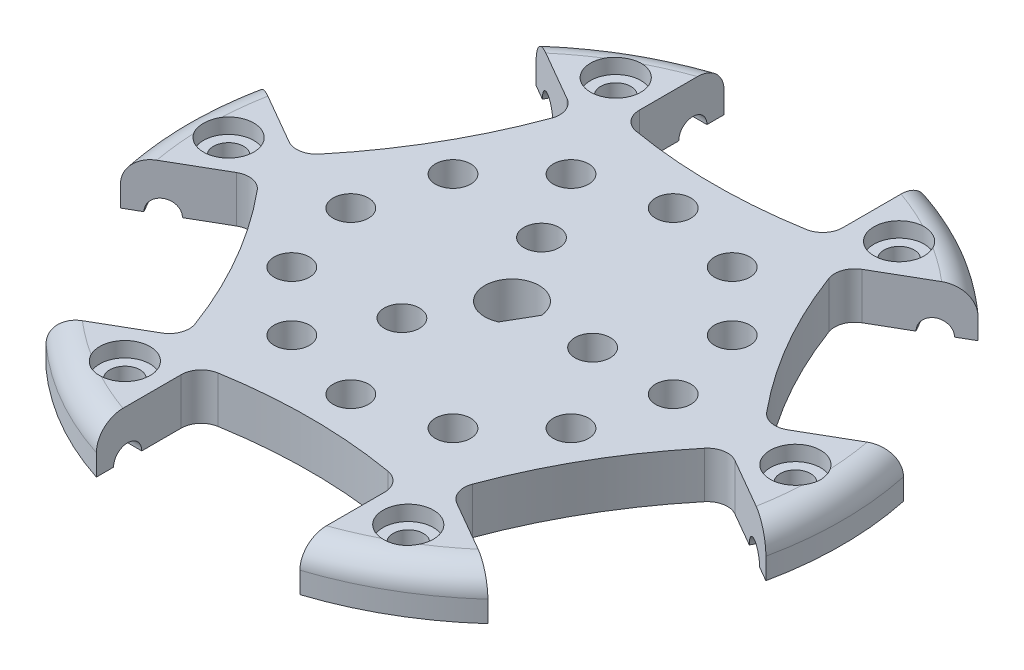
SolidWorks part; units mm, degrees
ref_plane "Plano frontal" through (0, 0, 0) normal (0, 0, 1) x (1, 0, 0)
ref_plane "Plano superior" through (0, 0, 0) normal (0, 1, 0) x (1, 0, 0)
ref_plane "Plano direito" through (0, 0, 0) normal (1, 0, 0) x (0, 0, -1)
sketch "Esboço1" plane through (0, 0, 0) normal (0, 0, 1) x (1, 0, 0)
  line L1 (-32.75, 2.1) -> (-32.75, 0)
  line L2 (-30.25, 4.6) -> (-6.07, 4.6)
  line L15 (-6.07, 4.6) -> (0, 4.6)
  line L17 (0, 0) -> (0, 4.6)
  line L18 (-32.75, 0) -> (0, 0)
  arc A3 (-30.25, 4.6) -> (-32.75, 2.1) centre (-30.25, 2.1) ccw
revolve "Revolução3" add sketch "Esboço1" angle 360 about L17
sketch "Esboço3" plane through (0, 0, 0) normal (0, -1, 0) x (1, 0, 0)
  line L2 (-10.1, 71.55) -> (10.1, 71.55)
  line L3 (-10.1, 71.55) -> (-10.1, 22.7384)
  line L4 (10.1, 71.55) -> (10.1, 22.7384)
  line L5 (10.1, -71.55) -> (-10.1, -71.55)
  line L6 (10.1, -71.55) -> (10.1, -22.7384)
  line L7 (-10.1, -71.55) -> (-10.1, -22.7384)
  line L10 (56.9141, 44.5219) -> (67.0141, 27.0281)
  line L11 (56.9141, 44.5219) -> (14.642, 20.116)
  line L12 (67.0141, 27.0281) -> (24.742, 2.6223)
  line L13 (-56.9141, -44.5219) -> (-67.0141, -27.0281)
  line L14 (-56.9141, -44.5219) -> (-14.642, -20.116)
  line L15 (-67.0141, -27.0281) -> (-24.742, -2.6223)
  line L18 (-67.0141, 27.0281) -> (-56.9141, 44.5219)
  line L19 (-67.0141, 27.0281) -> (-24.742, 2.6223)
  line L20 (-56.9141, 44.5219) -> (-14.642, 20.116)
  line L21 (67.0141, -27.0281) -> (56.9141, -44.5219)
  line L22 (67.0141, -27.0281) -> (24.742, -2.6223)
  line L23 (56.9141, -44.5219) -> (14.642, -20.116)
  arc A1 (-8.4375, 20.7671) -> (8.4375, 20.7671) centre (0, 70.05) ccw
  arc A2 (8.4375, 20.7671) -> (10.1, 22.7384) centre (8.1, 22.7384) ccw
  arc A3 (-8.4375, 20.7671) -> (-10.1, 22.7384) centre (-8.1, 22.7384) cw
  arc A4 (8.4375, -20.7671) -> (-8.4375, -20.7671) centre (0, -70.05) ccw
  arc A5 (-8.4375, -20.7671) -> (-10.1, -22.7384) centre (-8.1, -22.7384) ccw
  arc A6 (8.4375, -20.7671) -> (10.1, -22.7384) centre (8.1, -22.7384) cw
  arc A7 (13.766, 17.6906) -> (22.2035, 3.0764) centre (60.6651, 35.025) ccw
  arc A8 (22.2035, 3.0764) -> (24.742, 2.6223) centre (23.742, 4.3544) ccw
  arc A9 (13.766, 17.6906) -> (14.642, 20.116) centre (15.642, 18.384) cw
  arc A10 (-13.766, -17.6906) -> (-22.2035, -3.0764) centre (-60.6651, -35.025) ccw
  arc A11 (-22.2035, -3.0764) -> (-24.742, -2.6223) centre (-23.742, -4.3544) ccw
  arc A12 (-13.766, -17.6906) -> (-14.642, -20.116) centre (-15.642, -18.384) cw
  arc A13 (-22.2035, 3.0764) -> (-13.766, 17.6906) centre (-60.6651, 35.025) ccw
  arc A14 (-13.766, 17.6906) -> (-14.642, 20.116) centre (-15.642, 18.384) ccw
  arc A15 (-22.2035, 3.0764) -> (-24.742, 2.6223) centre (-23.742, 4.3544) cw
  arc A16 (22.2035, -3.0764) -> (13.766, -17.6906) centre (60.6651, -35.025) ccw
  arc A17 (13.766, -17.6906) -> (14.642, -20.116) centre (15.642, -18.384) ccw
  arc A18 (22.2035, -3.0764) -> (24.742, -2.6223) centre (23.742, -4.3544) cw
extrude "Corte-extrusão2" cut sketch "Esboço3" against normal blind 10
sketch "Esboço5" plane through (0, 0, 0) normal (0, -1, 0) x (1, 0, 0)
  line L0 (-12.6, 26.65) -> (12.6, 26.65)
  line L1 (-12.6, 28.05) -> (12.6, 28.05)
  line L10 (-12.6, 28.05) -> (-12.6, 26.65)
  line L13 (12.6, 28.05) -> (12.6, 26.65)
revolve "Corte-Revolução3" cut sketch "Esboço5" angle 360 about L1
sketch "Esboço6" plane through (0, 0, 0) normal (0, -1, 0) x (1, 0, 0)
  line L21 (-29.3796, 2.4131) -> (-16.7796, 24.2369)
  line L22 (-30.592, 3.1131) -> (-17.992, 24.9369)
  line L23 (-30.592, 3.1131) -> (-29.3796, 2.4131)
  line L24 (-17.992, 24.9369) -> (-16.7796, 24.2369)
revolve "Corte-Revolução4" cut sketch "Esboço6" angle 360 about L22
sketch "Esboço7" plane through (0, 0, 0) normal (0, -1, 0) x (1, 0, 0)
  line L9 (-16.7796, -24.2369) -> (-29.3796, -2.4131)
  line L10 (-17.992, -24.9369) -> (-30.592, -3.1131)
  line L11 (-17.992, -24.9369) -> (-16.7796, -24.2369)
  line L12 (-30.592, -3.1131) -> (-29.3796, -2.4131)
revolve "Corte-Revolução5" cut sketch "Esboço7" angle 360 about L10
sketch "Esboço8" plane through (0, 0, 0) normal (0, -1, 0) x (1, 0, 0)
  line L13 (16.7796, 24.2369) -> (29.3796, 2.4131)
  line L14 (17.992, 24.9369) -> (30.592, 3.1131)
  line L15 (17.992, 24.9369) -> (16.7796, 24.2369)
  line L16 (30.592, 3.1131) -> (29.3796, 2.4131)
revolve "Corte-Revolução6" cut sketch "Esboço8" angle 360 about L14
sketch "Esboço10" plane through (0, 0, 0) normal (0, -1, 0) x (1, 0, 0)
  line L1 (12.6, -26.65) -> (-12.6, -26.65)
  line L2 (12.6, -28.05) -> (-12.6, -28.05)
  line L3 (12.6, -28.05) -> (12.6, -26.65)
  line L4 (-12.6, -28.05) -> (-12.6, -26.65)
revolve "Corte-Revolução7" cut sketch "Esboço10" angle 360 about L2
sketch "Esboço11" plane through (0, 0, 0) normal (0, -1, 0) x (1, 0, 0)
  line L5 (29.3796, -2.4131) -> (16.7796, -24.2369)
  line L6 (30.592, -3.1131) -> (17.992, -24.9369)
  line L7 (30.592, -3.1131) -> (29.3796, -2.4131)
  line L8 (17.992, -24.9369) -> (16.7796, -24.2369)
revolve "Corte-Revolução8" cut sketch "Esboço11" angle 360 about L6
sketch "Esboço12" plane through (0, 0, 0) normal (0, -1, 0) x (1, 0, 0)
  circle A1 centre (0, 16) radius 1.75
  circle A2 centre (-8, 13.8564) radius 1.75
  circle A3 centre (-13.8564, 8) radius 1.75
  circle A4 centre (-16, 0) radius 1.75
  circle A5 centre (-13.8564, -8) radius 1.75
  circle A6 centre (-8, -13.8564) radius 1.75
  circle A7 centre (0, -16) radius 1.75
  circle A8 centre (8, -13.8564) radius 1.75
  circle A9 centre (13.8564, -8) radius 1.75
  circle A10 centre (16, 0) radius 1.75
  circle A11 centre (13.8564, 8) radius 1.75
  circle A12 centre (8, 13.8564) radius 1.75
  circle A13 centre (28.1296, 0) radius 1.3
  circle A14 centre (14.0648, 24.3609) radius 1.3
  circle A15 centre (-14.0648, 24.3609) radius 1.3
  circle A16 centre (-28.1296, 0) radius 1.3
  circle A18 centre (14.0648, -24.3609) radius 1.3
  circle A19 centre (-14.0648, -24.3609) radius 1.3
sketch "Esboço14" plane through (0, 0, 0) normal (0, -1, 0) x (1, 0, 0)
  line L2 (1.0522, 2.3776) -> (2.5851, -0.2776)
  arc A0 (1.0522, 2.3776) -> (2.5851, -0.2776) centre (0, 0) ccw
extrude "Corte-extrusão7" cut sketch "Esboço12" against normal through all
sketch "Esboço15" plane through (0, 4.6, 0) normal (0, 1, 0) x (1, 0, 0)
  line L0 (0, 0) -> (-1.5171, -0.4065)
  circle A0 centre (-4, -6.9282) radius 1.75
  circle A1 centre (8, 0) radius 1.75
  circle A2 centre (-4, 6.9282) radius 1.75
extrude "Corte-extrusão8" cut sketch "Esboço15" against normal through all contours A0 | A1 | A2
extrude "Corte-extrusão9" cut sketch "Esboço14" against normal through all
sketch "Esboço16" plane through (0, 4.6, 0) normal (0, 1, 0) x (1, 0, 0)
  circle A0 centre (-14.0648, 24.3609) radius 2.05
  circle A1 centre (-28.1296, 0) radius 2.05
  circle A2 centre (-14.0648, -24.3609) radius 2.05
  circle A3 centre (14.0648, -24.3609) radius 2.05
  circle A4 centre (28.1296, 0) radius 2.05
  circle A5 centre (14.0648, 24.3609) radius 2.05
extrude "Corte-extrusão10" cut sketch "Esboço16" against normal blind 1.5
sketch "Esboço17" plane through (0, 4.6, 0) normal (0, 1, 0) x (1, 0, 0)
  circle A0 centre (-14.0648, 24.3609) radius 1.5
  circle A1 centre (14.0648, 24.3609) radius 1.5
  circle A2 centre (-14.0648, -24.3609) radius 1.5
  circle A3 centre (14.0648, -24.3609) radius 1.5
  circle A4 centre (-28.1296, 0) radius 1.5
  circle A5 centre (28.1296, 0) radius 1.5
extrude "Corte-extrusão11" cut sketch "Esboço17" against normal through all
sketch "Esboço18" plane through (0, 4.6, 0) normal (0, 1, 0) x (1, 0, 0)
  circle A0 centre (-14.0648, 24.3609) radius 2.5
  circle A1 centre (14.0648, 24.3609) radius 2.5
  circle A2 centre (14.0648, -24.3609) radius 2.5
  circle A3 centre (-14.0648, -24.3609) radius 2.5
  circle A4 centre (-28.1296, 0) radius 2.5
  circle A5 centre (28.1296, 0) radius 2.5
extrude "Corte-extrusão12" cut sketch "Esboço18" against normal blind 1.5
sketch "Esboço19" plane through (0, 4.6, 0) normal (0, 1, 0) x (1, 0, 0)
  line L2 (1.1226, -2.4555) -> (2.6879, 0.2555)
  arc A0 (2.6879, 0.2555) -> (1.1226, -2.4555) centre (0, 0) ccw
extrude "Corte-extrusão13" cut sketch "Esboço19" against normal through all
